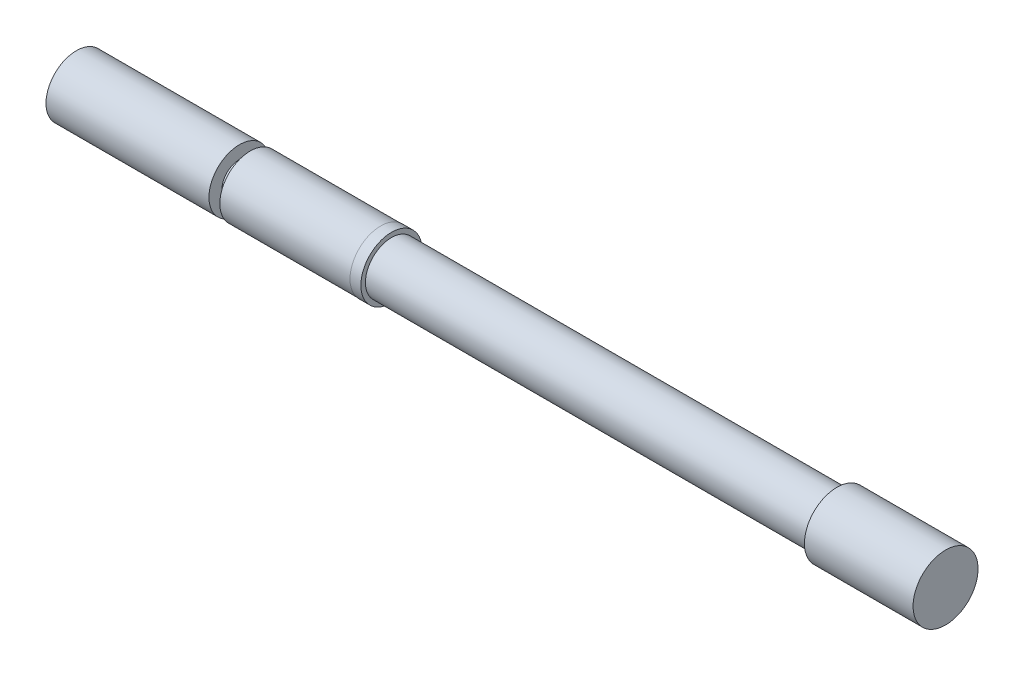
SolidWorks part; units mm, degrees
ref_plane "Front Plane" through (0, 0, 0) normal (0, 0, 1) x (1, 0, 0)
ref_plane "Top Plane" through (0, 0, 0) normal (0, 1, 0) x (1, 0, 0)
ref_plane "Right Plane" through (0, 0, 0) normal (1, 0, 0) x (0, 0, -1)
sketch "Sketch3" plane through (0, 0, 0) normal (0, 0, 1) x (1, 0, 0)
  line L0 (0, 0) -> (400, 0)
  line L1 (0, 0) -> (0, 14)
  line L2 (0, 14) -> (75, 14)
  line L3 (75, 14) -> (75, 8.0867)
  line L4 (75, 8.0867) -> (80, 8.0867)
  line L5 (80, 8.0867) -> (80, 14)
  line L6 (80, 14) -> (140, 14)
  line L7 (140, 14) -> (140, 14.0947)
  line L8 (140, 14.0947) -> (145, 14.0947)
  line L9 (145, 14.0947) -> (145, 12)
  line L10 (145, 12) -> (350, 12)
  line L11 (350, 12) -> (350, 14.9567)
  line L12 (350, 14.9567) -> (400, 14.9567)
  line L13 (400, 14.9567) -> (400, 0)
  point P3 (0, 0)
  point P16 (145, 12)
  dimension "D1" = 400
  dimension "D2" = 14
  dimension "D3" = 12
  dimension "D4" = 5
  dimension "D5" = 5
  dimension "D6" = 75
  dimension "D7" = 60
  dimension "D8" = 205
revolve "Revolve1" add sketch "Sketch3" angle 360 about L0
